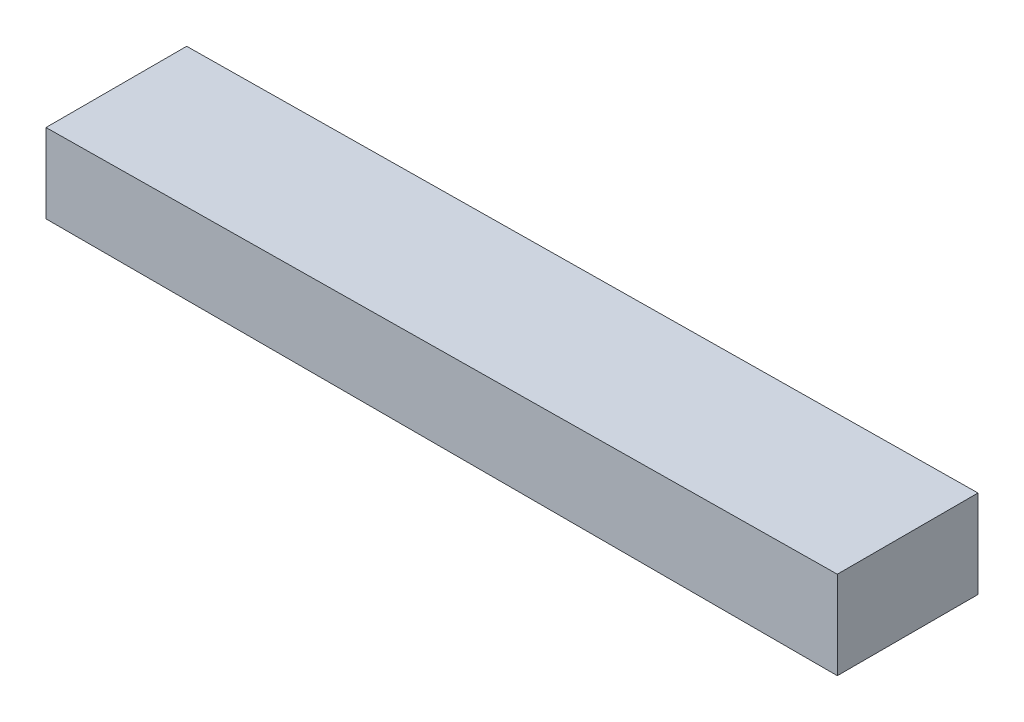
SolidWorks part; units mm, degrees
ref_plane "Front Plane" through (0, 0, 0) normal (0, 0, 1) x (1, 0, 0)
ref_plane "Top Plane" through (0, 0, 0) normal (0, 1, 0) x (1, 0, 0)
ref_plane "Right Plane" through (0, 0, 0) normal (1, 0, 0) x (0, 0, -1)
sketch "Sketch1" plane through (0, 0, 0) normal (0, 0, 1) x (1, 0, 0)
  line L0 (0, 0) -> (90, 0)
  line L1 (90, 0) -> (90, 10)
  line L2 (90, 10) -> (0, 9)
  line L3 (0, 9) -> (0, 0)
  dimension "D1" = 90
  dimension "D2" = 10
  dimension "D3" = 9
extrude "Boss-Extrude1" add sketch "Sketch1" along normal blind 16
